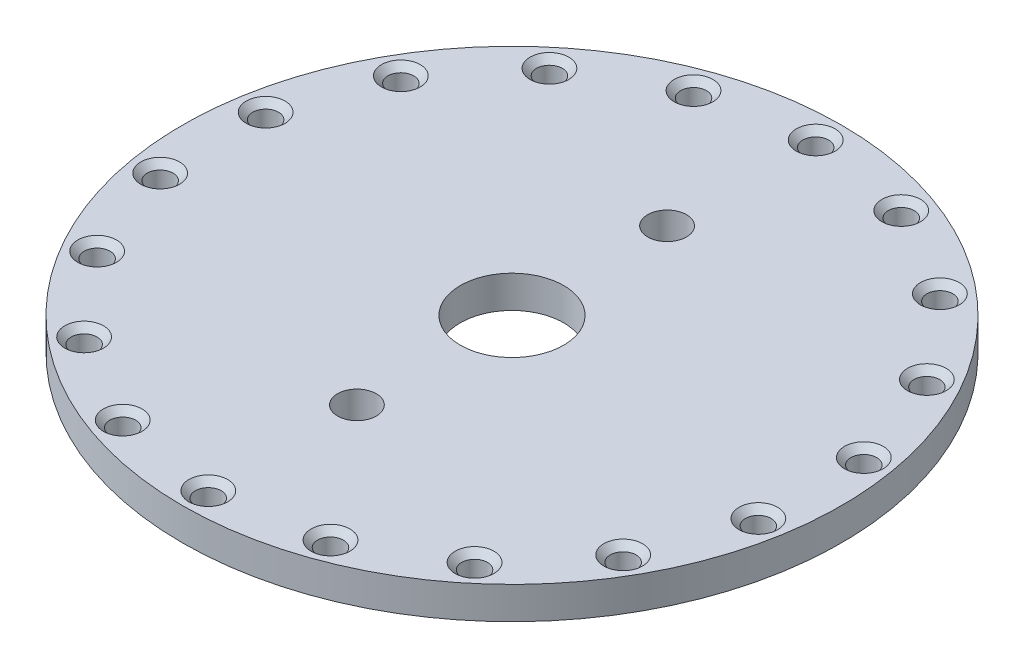
SolidWorks part; units mm, degrees
material "Plain Carbon Steel"
ref_plane "Front Plane" through (0, 0, 0) normal (0, 0, 1) x (1, 0, 0)
ref_plane "Top Plane" through (0, 0, 0) normal (0, 1, 0) x (1, 0, 0)
ref_plane "Right Plane" through (0, 0, 0) normal (1, 0, 0) x (0, 0, -1)
sketch "Sketch1" plane through (0, 0, 0) normal (0, 1, 0) x (1, 0, 0)
  circle A0 centre (0, 0) radius 25.5
  dimension "D1" = 51
sketch "Sketch2" plane through (0, 0, 0) normal (0, 1, 0) x (1, 0, 0)
  circle A0 centre (0, 0) radius 4
  dimension "D1" = 8
sketch "Sketch3" plane through (0, 0, 0) normal (0, 1, 0) x (1, 0, 0)
  line L0 (0, 0) -> (0, 12) construction
  circle A0 centre (0, 12) radius 1.5
  circle A1 centre (0, -12) radius 1.5
  point P8 (0, 0)
  dimension "D1" = 3
  dimension "D2" = 12
  dimension "D3" = 2
sketch "Sketch4" plane through (0, 0, 0) normal (0, 1, 0) x (1, 0, 0)
  line L0 (0, 25.5) -> (0, 23.5) construction
  line L1 (0, 23.5) -> (0, 0) construction
  circle A0 centre (0, 23.5) radius 1
  circle A1 centre (0, 0) radius 25.5 construction
  circle A2 centre (8.0375, 22.0828) radius 1
  circle A3 centre (15.1055, 18.002) radius 1
  circle A4 centre (20.3516, 11.75) radius 1
  circle A5 centre (23.143, 4.0807) radius 1
  circle A6 centre (23.143, -4.0807) radius 1
  circle A7 centre (20.3516, -11.75) radius 1
  circle A8 centre (15.1055, -18.002) radius 1
  circle A9 centre (8.0375, -22.0828) radius 1
  circle A10 centre (0, -23.5) radius 1
  circle A11 centre (-8.0375, -22.0828) radius 1
  circle A12 centre (-15.1055, -18.002) radius 1
  circle A13 centre (-20.3516, -11.75) radius 1
  circle A14 centre (-23.143, -4.0807) radius 1
  circle A15 centre (-23.143, 4.0807) radius 1
  circle A16 centre (-20.3516, 11.75) radius 1
  circle A17 centre (-15.1055, 18.002) radius 1
  circle A18 centre (-8.0375, 22.0828) radius 1
  point P43 (0, 0)
  dimension "D2" = 2
  dimension "D1" = 2
  dimension "D3" = 18
extrude "Boss-Extrude1" add sketch "Sketch1" along normal blind 2.5
extrude "Cut-Extrude1" cut sketch "Sketch2" along normal up to next
extrude "Cut-Extrude2" cut sketch "Sketch3" along normal up to next
extrude "Cut-Extrude3" cut sketch "Sketch4" along normal up to next
chamfer "Chamfer1" distance 0.5 angle 45 36 edges at (-20.3516, 0, -10.75) (-20.3516, 2.5, -10.75) (-15.1055, 0, -17.002) (-15.1055, 2.5, -17.002) (-8.0375, 0, -21.0828) (-8.0375, 2.5, -21.0828) (0, 0, -22.5) (0, 2.5, -22.5) (8.0375, 0, -21.0828) (8.0375, 2.5, -21.0828) (15.1055, 0, -17.002) (15.1055, 2.5, -17.002) (20.3516, 0, -10.75) (20.3516, 2.5, -10.75) (23.143, 0, -3.0807) (23.143, 2.5, -3.0807) (23.143, 0, 5.0807) (23.143, 2.5, 5.0807) (20.3516, 0, 12.75) (20.3516, 2.5, 12.75) (15.1055, 0, 19.002) (15.1055, 2.5, 19.002) (8.0375, 0, 23.0828) (8.0375, 2.5, 23.0828) (0, 0, 24.5) (0, 2.5, 24.5) (-8.0375, 0, 23.0828) (-8.0375, 2.5, 23.0828) (-15.1055, 0, 19.002) (-15.1055, 2.5, 19.002) (-20.3516, 0, 12.75) (-20.3516, 2.5, 12.75) (-23.143, 0, 5.0807) (-23.143, 2.5, 5.0807) (-23.143, 0, -3.0807) (-23.143, 2.5, -3.0807)
